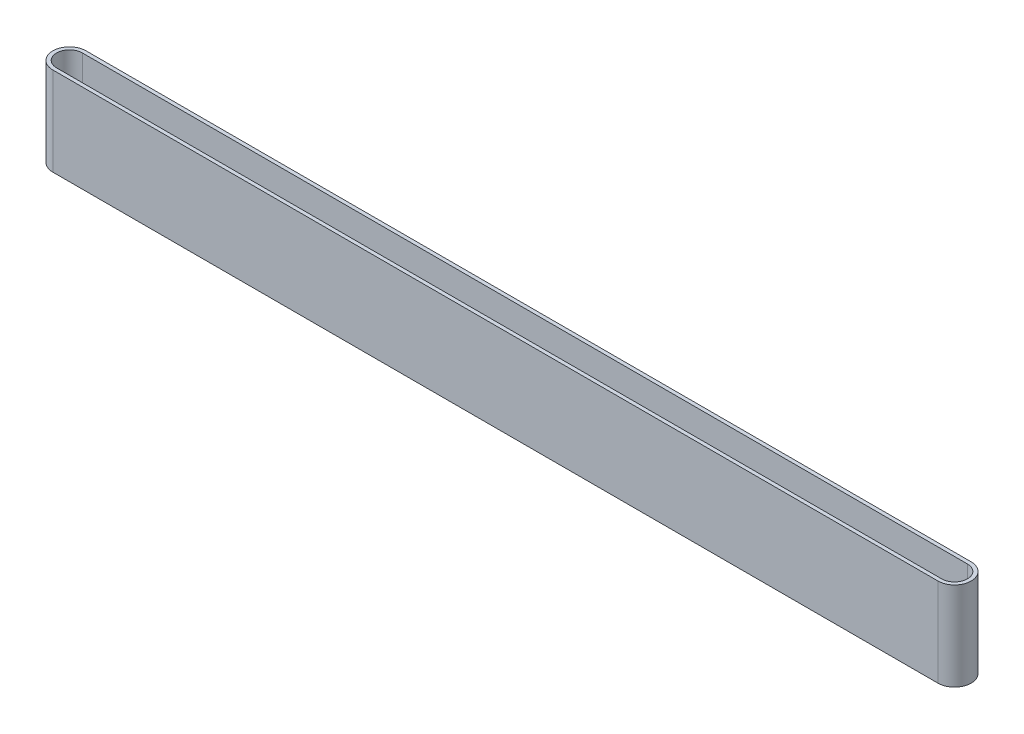
SolidWorks part; units mm, degrees
material "SBR"
ref_plane "Front Plane" through (0, 0, 0) normal (0, 0, 1) x (1, 0, 0)
ref_plane "Top Plane" through (0, 0, 0) normal (0, 1, 0) x (1, 0, 0)
ref_plane "Right Plane" through (0, 0, 0) normal (1, 0, 0) x (0, 0, -1)
sketch "Sketch1" plane through (0, 0, 0) normal (0, 1, 0) x (1, 0, 0)
  line L0 (0, 0) -> (762, 0) construction
  line L1 (0, 14.2875) -> (762, 14.2875)
  line L2 (0, -14.2875) -> (762, -14.2875)
  line L3 (0, 11.1125) -> (762, 11.1125)
  line L4 (0, -11.1125) -> (762, -11.1125)
  arc A0 (0, 14.2875) -> (0, -14.2875) centre (0, 0) ccw
  arc A1 (762, -14.2875) -> (762, 14.2875) centre (762, 0) ccw
  arc A2 (762, -11.1125) -> (762, 11.1125) centre (762, 0) ccw
  arc A3 (0, 11.1125) -> (0, -11.1125) centre (0, 0) ccw
  point P3 (381, 0)
  dimension "D1" = 14.2875
  dimension "D2" = 762
  dimension "D3" = 3.175
extrude "Boss-Extrude1" add sketch "Sketch1" along normal blind 76.2
